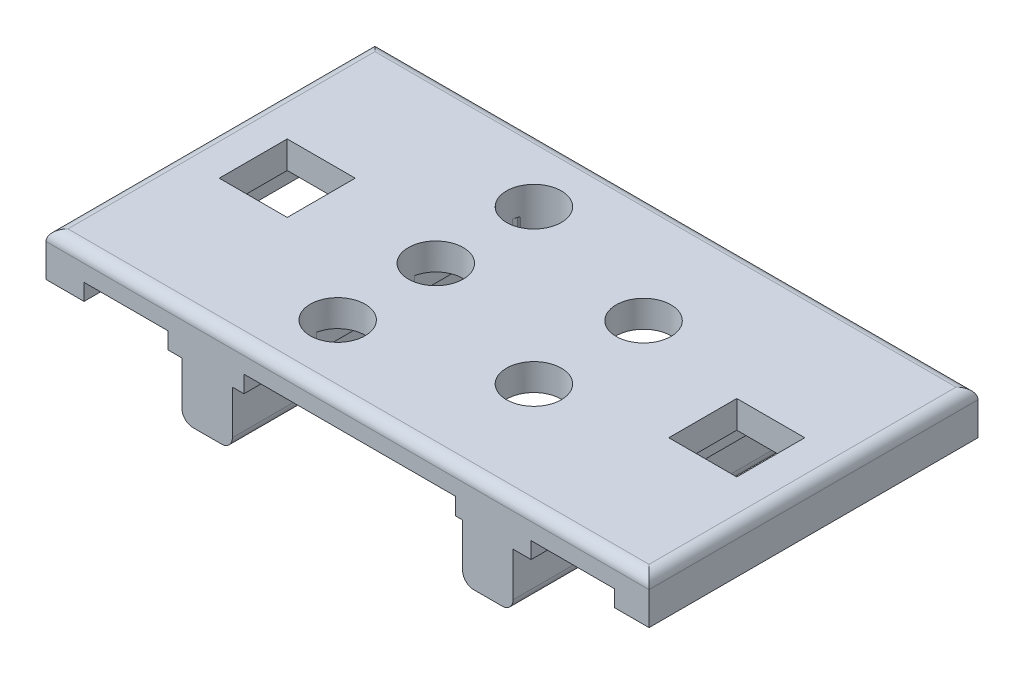
SolidWorks part; units mm, degrees
ref_plane "Front Plane" through (0, 0, 0) normal (0, 0, 1) x (1, 0, 0)
ref_plane "Top Plane" through (0, 0, 0) normal (0, 1, 0) x (1, 0, 0)
ref_plane "Right Plane" through (0, 0, 0) normal (1, 0, 0) x (0, 0, -1)
sketch "Sketch1" plane through (0, 0, 0) normal (0, 0, 1) x (1, 0, 0)
  line L0 (0, 0) -> (0, 35.9328) construction
  line L2 (-27.5, 2) -> (27.5, 2)
  line L3 (-27.5, 2) -> (-27.5, -2)
  line L4 (-27.5, -2) -> (27.5, -2)
  line L5 (27.5, 2) -> (27.5, -2)
  line L6 (-27.5, 2) -> (27.5, -2) construction
  line L7 (-27.5, -2) -> (27.5, 2) construction
  line L8 (-15.1, -2) -> (-10.5, -2)
  line L9 (-15.1, -2) -> (-15.1, -7)
  line L10 (-15.1, -7) -> (-10.5, -7)
  line L11 (-10.5, -2) -> (-10.5, -7)
  line L12 (10.5, -2) -> (15.1, -2)
  line L13 (10.5, -2) -> (10.5, -7)
  line L14 (10.5, -7) -> (15.1, -7)
  line L15 (15.1, -2) -> (15.1, -7)
  dimension "D1" = 4
  dimension "D2" = 55
  dimension "D3" = 5
  dimension "D4" = 4.6
  dimension "D5" = 5
  dimension "D6" = 4.6
  dimension "D7" = 21
  dimension "D8" = 10.5
extrude "Boss-Extrude2" add sketch "Sketch1" along normal blind 30 contours L5 L2 L3 L4 | L11 L4 L9 L10 | L15 L4 L13 L14
fillet "Fillet1" radius 1 8 edges at (-10.5, -7, 15) (10.5, -7, 15) (15.1, -7, 15) (-15.1, -7, 15) (27.5, 2, 15) (0, 2, 0) (0, 2, 30) (-27.5, 2, 15)
ref_plane "Plane1" through (0, 0, 10) normal (0, 0, 1) x (1, 0, 0)
sketch "Sketch2" plane through (0, 2, 0) normal (0, 1, 0) x (1, 0, 0)
  line L0 (0, 0) -> (0, -29) construction
  line L1 (-26.5, -29) -> (26.5, -29) construction
  line L2 (-26.5, -15) -> (26.5, -15) construction
  line L3 (-26.5, -1) -> (-26.5, -29) construction
  line L4 (26.5, -29) -> (26.5, -1) construction
  line L10 (26.5, -1) -> (-26.5, -1) construction
  line L11 (-23.6, -11.9) -> (-17.4, -11.9)
  line L16 (-23.6, -11.9) -> (-23.6, -18.1)
  line L17 (-23.6, -18.1) -> (-17.4, -18.1)
  line L18 (-17.4, -11.9) -> (-17.4, -18.1)
  line L19 (-23.6, -11.9) -> (-17.4, -18.1) construction
  line L20 (-23.6, -18.1) -> (-17.4, -11.9) construction
  line L21 (23.6, -18.1) -> (17.4, -18.1)
  line L22 (17.4, -11.9) -> (17.4, -18.1)
  line L23 (23.6, -11.9) -> (17.4, -11.9)
  line L24 (23.6, -11.9) -> (23.6, -18.1)
  circle A3 centre (-7, -6) radius 2.5
  circle A4 centre (-7, -14.9493) radius 2.5
  circle A5 centre (-7, -23.8986) radius 2.5
  circle A8 centre (7, -20) radius 2.5
  circle A9 centre (7, -10) radius 2.5
  point P11 (-20.5, -15)
  dimension "D4" = 5
  dimension "D5" = 5
  dimension "D1" = 6.2
  dimension "D2" = 6.2
  dimension "D3" = 6
  dimension "D6" = 7
  dimension "D8" = 5
extrude "Cut-Extrude1" cut sketch "Sketch2" against normal blind 10
sketch "Sketch4" plane through (0, 0, 30) normal (0, 0, 1) x (1, 0, 0)
  line L1 (-9.4479, -0.4497) -> (9.8474, -0.4497)
  line L2 (-9.4479, -0.4497) -> (-9.4479, -2)
  line L3 (-9.4479, -2) -> (9.8474, -2)
  line L4 (9.8474, -0.4497) -> (9.8474, -2)
  line L5 (-10.5, -2) -> (10.5, -2) construction
  line L6 (-27.5, -2) -> (-15.1, -2) construction
  line L7 (-24.0297, -0.491) -> (-16.3918, -0.491)
  line L8 (-24.0297, -0.491) -> (-24.0297, -2)
  line L9 (-24.0297, -2) -> (-16.3918, -2)
  line L10 (-16.3918, -0.491) -> (-16.3918, -2)
  line L11 (15.1, -2) -> (27.5, -2) construction
  line L12 (16.7473, -0.5048) -> (24.3482, -0.5048)
  line L13 (16.7473, -0.5048) -> (16.7473, -2)
  line L14 (16.7473, -2) -> (24.3482, -2)
  line L15 (24.3482, -0.5048) -> (24.3482, -2)
extrude "Cut-Extrude2" cut sketch "Sketch4" against normal blind 25
